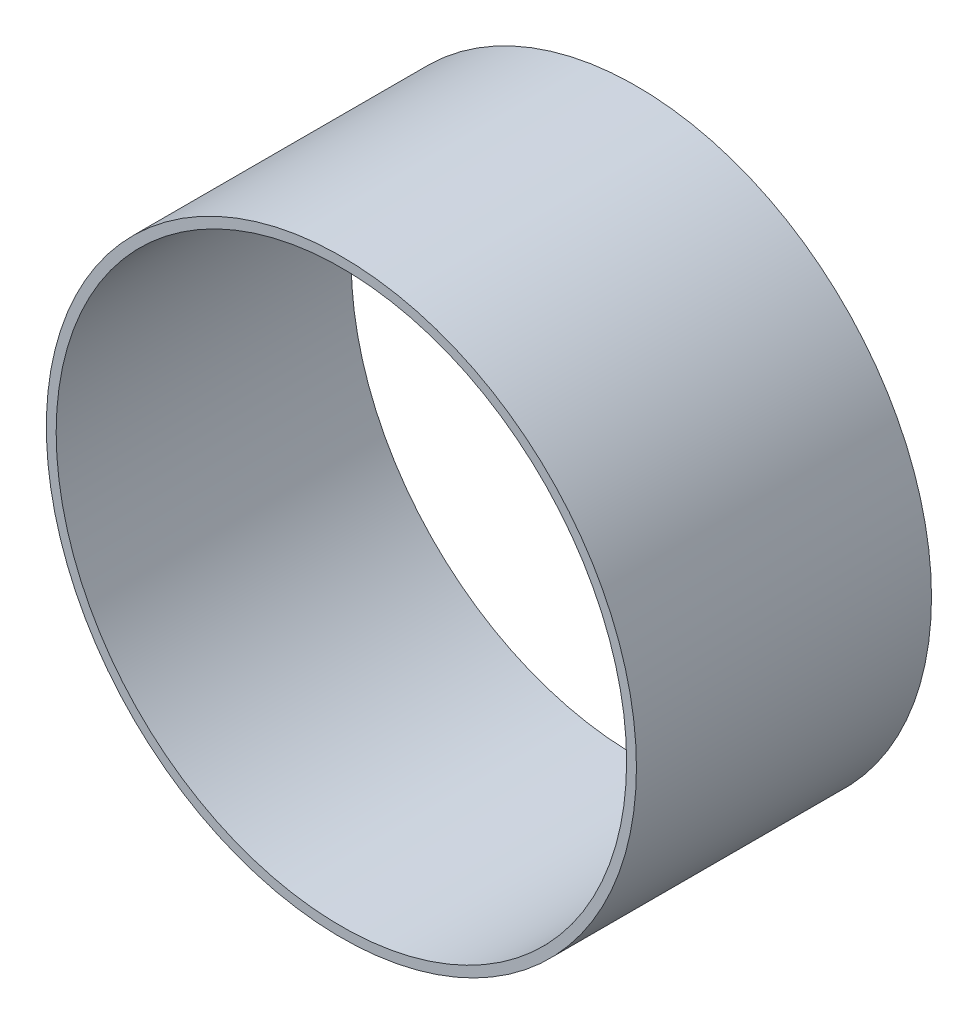
SolidWorks part; units mm, degrees
ref_plane "Front Plane" through (0, 0, 0) normal (0, 0, 1) x (1, 0, 0)
ref_plane "Top Plane" through (0, 0, 0) normal (0, 1, 0) x (1, 0, 0)
ref_plane "Right Plane" through (0, 0, 0) normal (1, 0, 0) x (0, 0, -1)
sketch "Sketch1" plane through (0, 0, 0) normal (0, 0, 1) x (1, 0, 0)
  circle A0 centre (0, 0) radius 120
  circle A1 centre (0, 0) radius 116
  dimension "D1" = 240
  dimension "D2" = 232
extrude "Boss-Extrude1" add sketch "Sketch1" along normal blind 120
